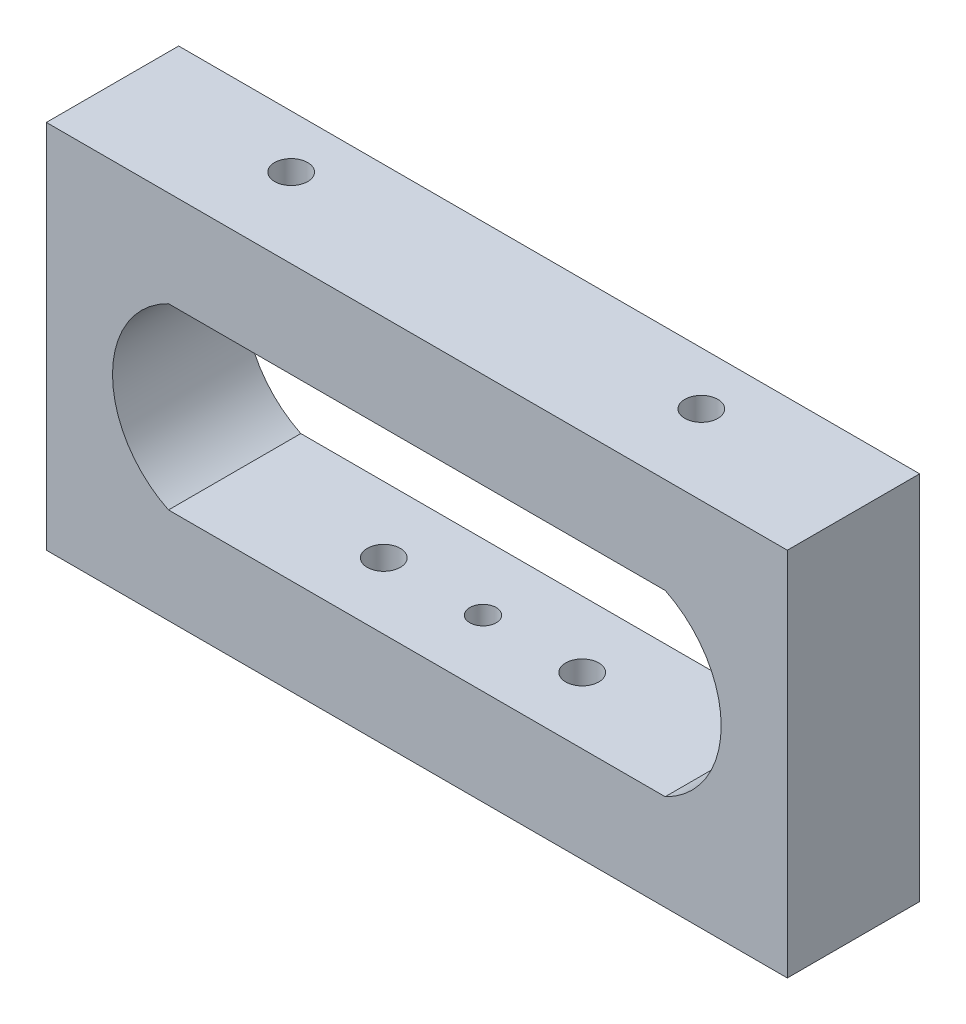
SolidWorks part; units mm, degrees
ref_plane "Front Plane" through (0, 0, 0) normal (0, 0, 1) x (1, 0, 0)
ref_plane "Top Plane" through (0, 0, 0) normal (0, 1, 0) x (1, 0, 0)
ref_plane "Right Plane" through (0, 0, 0) normal (1, 0, 0) x (0, 0, -1)
sketch "Skizze1" plane through (0, 0, 0) normal (0, 0, 1) x (1, 0, 0)
  line L1 (-28, 14) -> (28, 14)
  line L2 (-28, 14) -> (-28, -14)
  line L3 (-28, -14) -> (28, -14)
  line L4 (28, 14) -> (28, -14)
  line L5 (0, -14) -> (0, 14) construction
  line L6 (-28, 0) -> (28, 0) construction
  point P60 (0, 0)
  dimension "D1" = 28
  dimension "D2" = 56
extrude "Aufsatz-Linear austragen1" add sketch "Skizze1" along normal blind 10
sketch "Skizze2" plane through (0, 0, 0) normal (0, 0, -1) x (-1, 0, 0)
  line L0 (28, 14) -> (28, -14) construction
  line L1 (-18.7692, 6.75) -> (18.7692, 6.75)
  line L3 (-18.7692, -6.75) -> (18.7692, -6.75)
  line L5 (0, -6.75) -> (0, 6.75) construction
  line L6 (-23, 0) -> (23, 0) construction
  line L7 (-28, -14) -> (-28, 14) construction
  line L8 (28, -14) -> (-28, -14) construction
  arc A0 (-18.7692, 6.75) -> (-18.7692, -6.75) centre (-15.5, 0) ccw
  arc A1 (18.7692, 6.75) -> (18.7692, -6.75) centre (15.5, 0) cw
  point P140 (0, 0)
  dimension "D4" = 15
  dimension "D1" = 13.5
  dimension "D2" = 31
  dimension "D3" = 14
extrude "Schnitt-Linear austragen1" cut sketch "Skizze2" against normal through all
hole_wizard "Kernloch für M3 Gewinde1" positions "Skizze3" profile "Skizze4" size "M3" standard "DIN" slot yes
sketch "Skizze3" plane through (0, -14, 0) normal (0, -1, 0) x (-1, 0, 0)
  line L0 (0, 0) -> (0, -10) construction
  line L1 (28, 0) -> (-28, 0) construction
  line L2 (28, -10) -> (-28, -10) construction
  line L4 (-28, -5) -> (28, -5) construction
  line L5 (-28, -10) -> (-28, 0) construction
  line L6 (28, -10) -> (28, 0) construction
  point P0 (-7.5, -5)
  point P2 (7.5, -5)
  dimension "D1" = 15
sketch "Skizze4" plane through (7.5, -14, 5) normal (1, 0, 0) x (0, 0, -1)
  line L0 (0, 0) -> (0, 9.2511)
  line L1 (0, 9.2511) -> (1.25, 8.5)
  line L2 (1.25, 8.5) -> (1.25, 0)
  line L5 (1.25, 0) -> (0, 0)
  line L10 (0, 9.2511) -> (-1.25, 8.5) construction
  line L11 (0, -6.35) -> (0, 107.95) construction
  dimension "Bohrerdurchmesser" = 2.5
  dimension "Bohrungstiefe" = 8.5
  dimension "Spitzenwinkel" = 118
hole_wizard "Kernloch für M3 Gewinde2" positions "Skizze7" profile "Skizze8" size "M3" standard "DIN"
sketch "Skizze7" plane through (0, 14, 0) normal (0, 1, 0) x (1, 0, 0)
  line L0 (28, -4) -> (-28, -4) construction
  line L5 (0, -10) -> (0, 0) construction
  line L6 (28, -10) -> (-28, -10) construction
  line L7 (28, 0) -> (-28, 0) construction
  line L8 (-28, -10) -> (-28, 0) construction
  line L9 (28, -10) -> (28, 0) construction
  point P0 (15.5, -4)
  point P23 (-15.5, -4)
  dimension "D1" = 31
  dimension "D2" = 4
sketch "Skizze8" plane through (15.5, 14, 4) normal (1, 0, 0) x (0, 0, 1)
  line L0 (0, 0) -> (0, 7.25)
  line L1 (0, 7.25) -> (1.25, 7.25)
  line L2 (1.25, 7.25) -> (1.25, 0)
  line L5 (1.25, 0) -> (0, 0)
  line L11 (0, -6.35) -> (0, 107.95) construction
  dimension "Bohrerdurchmesser" = 2.5
  dimension "Bohrungstiefe" = 7.25
hole_wizard "Ø2.0mm Stiftloch1" positions "Skizze9" profile "Skizze10" hole size "Ø2.0" standard "DIN"
sketch "Skizze9" plane through (0, -14, 0) normal (0, -1, 0) x (-1, 0, 0)
  line L0 (28, -5) -> (-28, -5) construction
  line L1 (28, -10) -> (28, 0) construction
  line L2 (-28, -10) -> (-28, 0) construction
  point P0 (0, -5)
sketch "Skizze10" plane through (0, -14, 5) normal (1, 0, 0) x (0, 0, -1)
  line L0 (0, 0) -> (0, 9.1009)
  line L1 (0, 9.1009) -> (1, 8.5)
  line L2 (1, 8.5) -> (1, 0)
  line L5 (1, 0) -> (0, 0)
  line L10 (0, 9.1009) -> (-1, 8.5) construction
  line L11 (0, -6.35) -> (0, 107.95) construction
  dimension "Bohrerdurchmesser" = 2
  dimension "Bohrungstiefe" = 8.5
  dimension "Spitzenwinkel" = 118
